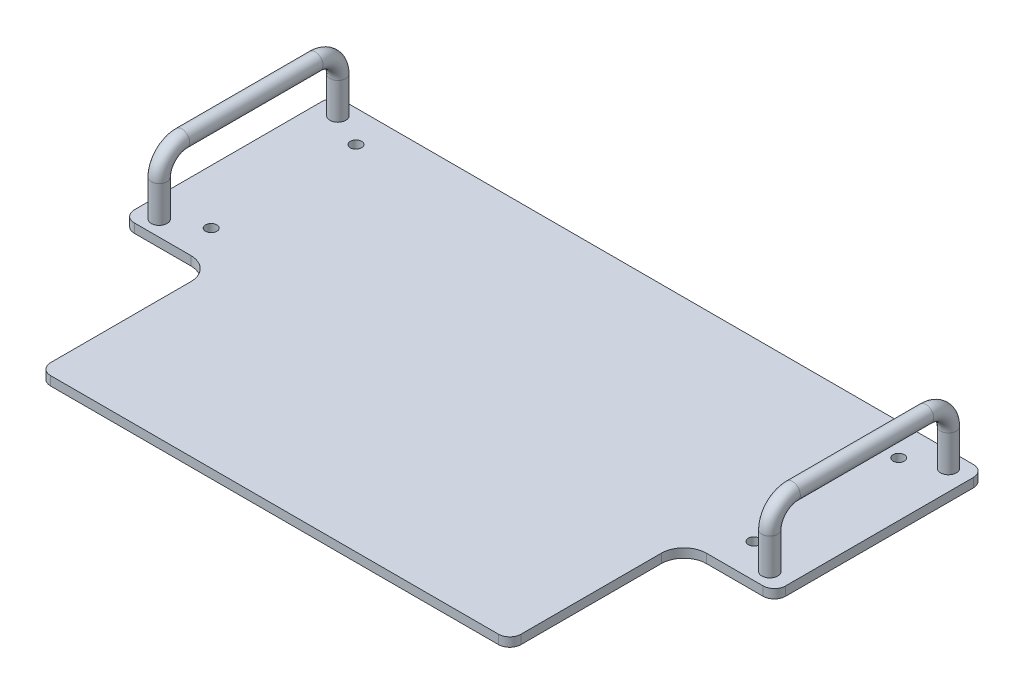
SolidWorks part; units mm, degrees
ref_plane "Front Plane" through (0, 0, 0) normal (0, 0, 1) x (1, 0, 0)
ref_plane "Top Plane" through (0, 0, 0) normal (0, 1, 0) x (1, 0, 0)
ref_plane "Right Plane" through (0, 0, 0) normal (1, 0, 0) x (0, 0, -1)
sketch "Esquisse1" plane through (0, 0, 0) normal (0, 1, 0) x (1, 0, 0)
  line L0 (5, 0) -> (203, 0)
  line L1 (208, 5) -> (208, 67)
  line L2 (218, 77) -> (243, 77)
  line L3 (248, 82) -> (248, 165)
  line L4 (-35, 170) -> (243, 170)
  line L5 (0, 5) -> (0, 67)
  line L6 (-10, 77) -> (-35, 77)
  line L7 (-40, 82) -> (-40, 165)
  arc A0 (243, 77) -> (248, 82) centre (243, 82) ccw
  arc A1 (248, 165) -> (243, 170) centre (243, 165) ccw
  arc A2 (-40, 165) -> (-35, 170) centre (-35, 165) cw
  arc A3 (-35, 77) -> (-40, 82) centre (-35, 82) cw
  arc A4 (5, 0) -> (0, 5) centre (5, 5) cw
  arc A5 (203, 0) -> (208, 5) centre (203, 5) ccw
  arc A6 (0, 67) -> (-10, 77) centre (-10, 67) ccw
  arc A7 (208, 67) -> (218, 77) centre (218, 67) cw
  point P11 (248, 77)
  point P14 (248, 170)
  point P19 (-40, 77)
  point P22 (0, 0)
  point P25 (208, 0)
  point P28 (0, 77)
  point P31 (208, 77)
  dimension "D7" = 5
  dimension "D8" = 10
  dimension "D1" = 208
  dimension "D2" = 77
  dimension "D3" = 40
  dimension "D4" = 93
  dimension "D5" = 77
  dimension "D6" = 40
extrude "Boss.-Extru.1" add sketch "Esquisse1" along normal blind 4 contours L4 A1 L3 A0 L2 A7 L1 A5 L0 A4 L5 A6 L6 A3 L7 A2
ref_plane "Plan1" through (0, 4, 0) normal (0, 1, 0) x (1, 0, 0)
sketch "Esquisse2" plane through (0, 4, 0) normal (0, 1, 0) x (1, 0, 0)
  line L0 (218, 77) -> (243, 77) construction
  line L2 (248, 82) -> (248, 165) construction
  line L3 (-35, 170) -> (243, 170) construction
  circle A0 centre (239, 163) radius 3.5
  circle A1 centre (239, 84) radius 3.5
  point P10 (230.5, 77)
  dimension "D1" = 7
  dimension "D2" = 7
  dimension "D5" = 7
  dimension "D7" = 9
  dimension "D8" = 9
  dimension "D9" = 7
ref_plane "Plan2" through (239, 0, 0) normal (1, 0, 0) x (0, 0, -1)
sketch "Esquisse11" plane through (0, 4, 0) normal (0, 1, 0) x (1, 0, 0)
  line L0 (-40, 82) -> (-40, 165) construction
  line L1 (-10, 77) -> (-35, 77) construction
  line L2 (-35, 170) -> (243, 170) construction
  circle A0 centre (-31, 84) radius 3.5
  circle A1 centre (-31, 163) radius 3.5
  dimension "D1" = 7
  dimension "D2" = 7
  dimension "D3" = 9
  dimension "D4" = 7
  dimension "D5" = 9
  dimension "D6" = 7
ref_plane "Plan4" through (239, 0, 0) normal (1, 0, 0) x (0, 0, -1)
sketch "Esquisse12" plane through (239, 0, 0) normal (1, 0, 0) x (0, 0, -1)
  line L0 (84, 4) -> (84, 20)
  line L1 (87.5, 4) -> (80.5, 4) construction
  line L2 (94, 30) -> (153, 30)
  line L3 (163, 20) -> (163, 4)
  line L4 (166.5, 4) -> (159.5, 4) construction
  line L5 (82, 4) -> (165, 4) construction
  arc A0 (153, 30) -> (163, 20) centre (153, 20) cw
  arc A1 (84, 20) -> (94, 30) centre (94, 20) cw
  dimension "D2" = 10
  dimension "D1" = 26
sweep "Balayage13" add path "Esquisse12" circular profile diameter 7 parameters "D3"=7
ref_plane "Plan5" through (-31, 0, 0) normal (-1, 0, 0) x (0, 0, 1)
sketch "Esquisse33" plane through (-31, 0, 0) normal (-1, 0, 0) x (0, 0, 1)
  line L0 (-163, 4) -> (-163, 20)
  line L1 (-159.5, 4) -> (-166.5, 4) construction
  line L2 (-153, 30) -> (-94, 30)
  line L3 (-84, 20) -> (-84, 4)
  line L4 (-80.5, 4) -> (-87.5, 4) construction
  line L5 (-82, 4) -> (-165, 4) construction
  arc A0 (-94, 30) -> (-84, 20) centre (-94, 20) cw
  arc A1 (-163, 20) -> (-153, 30) centre (-153, 20) cw
  dimension "D2" = 10
  dimension "D1" = 26
sweep "Balayage14" add path "Esquisse33" circular profile diameter 7 parameters "D3"=7
sketch "Esquisse34" plane through (0, 4, 0) normal (0, 1, 0) x (1, 0, 0)
  line L0 (248, 82) -> (248, 165) construction
  line L1 (-40, 82) -> (-40, 165) construction
  line L2 (-35, 170) -> (243, 170) construction
  line L3 (-10, 77) -> (-35, 77) construction
  line L4 (218, 77) -> (243, 77) construction
  circle A0 centre (-16, 156) radius 2.5
  circle A1 centre (224, 156) radius 2.5
  circle A2 centre (-16, 92) radius 2.5
  circle A3 centre (224, 92) radius 2.5
  dimension "D1" = 24
  dimension "D3" = 14
  dimension "D4" = 14
  dimension "D5" = 5
  dimension "D6" = 5
  dimension "D7" = 5
  dimension "D8" = 5
  dimension "D9" = 15
  dimension "D11" = 24
  dimension "D12" = 24
  dimension "D2" = 24
  dimension "D10" = 15
extrude "Enlèv. mat.-Extru.1" cut sketch "Esquisse34" against normal blind 10
